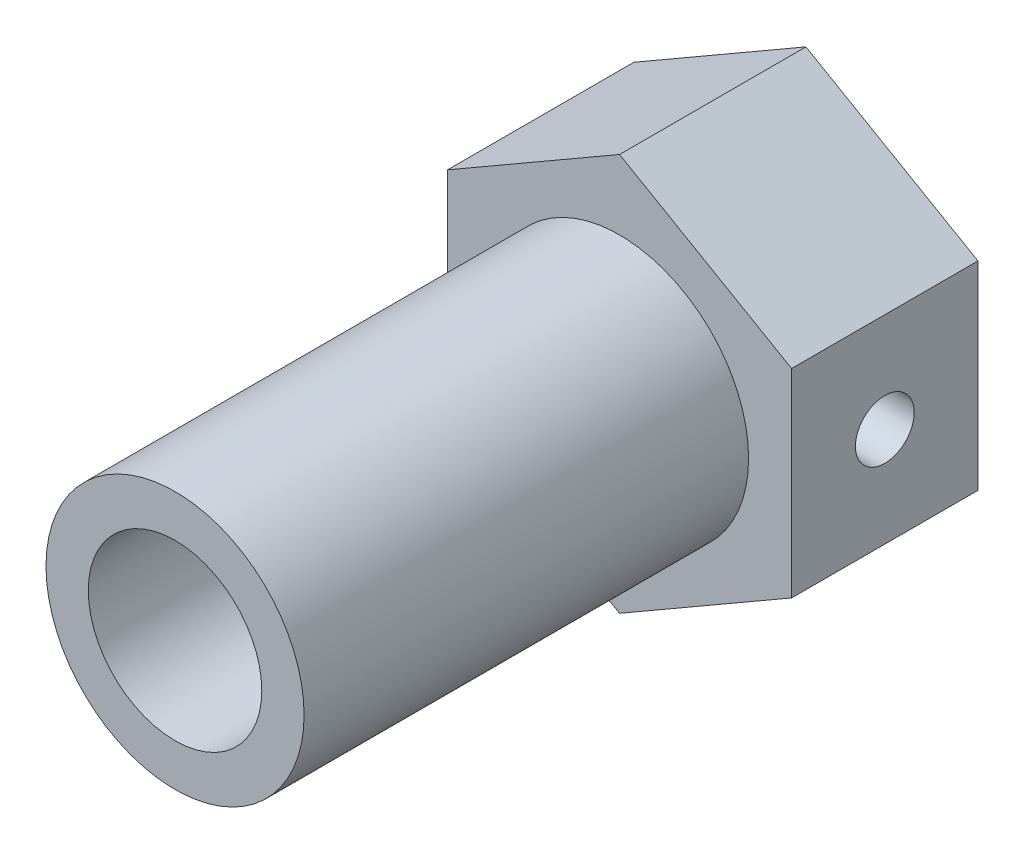
SolidWorks part; units mm, degrees
material "7050-T73510"
ref_plane "前视基准面" through (0, 0, 0) normal (0, 0, 1) x (1, 0, 0)
ref_plane "上视基准面" through (0, 0, 0) normal (0, 1, 0) x (1, 0, 0)
ref_plane "右视基准面" through (0, 0, 0) normal (1, 0, 0) x (0, 0, -1)
sketch "草图1" plane through (0, 0, 0) normal (0, 0, 1) x (1, 0, 0)
  line L1 (0, 13.8564) -> (-12, 6.9282)
  line L2 (-12, 6.9282) -> (-12, -6.9282)
  line L3 (-12, -6.9282) -> (0, -13.8564)
  line L4 (0, -13.8564) -> (12, -6.9282)
  line L5 (12, -6.9282) -> (12, 6.9282)
  line L6 (12, 6.9282) -> (0, 13.8564)
  circle A0 centre (0, 0) radius 12 construction
  dimension "D1" = 24
extrude "凸台-拉伸1" add sketch "草图1" along normal blind 13
sketch "草图2" plane through (0, 0, 13) normal (0, 0, 1) x (1, 0, 0)
  circle A0 centre (0, 0) radius 9
  dimension "D1" = 18
extrude "凸台-拉伸2" add sketch "草图2" along normal blind 31
sketch "草图3" plane through (0, 0, 0) normal (0, 0, -1) x (-1, 0, 0)
  circle A0 centre (0, 0) radius 8
  dimension "D1" = 16
extrude "凸台-拉伸3" add sketch "草图3" along normal blind 1
sketch "草图4" plane through (0, 0, -1) normal (0, 0, -1) x (-1, 0, 0)
  circle A0 centre (0, 0) radius 6.05
  dimension "D1" = 12.1
extrude "切除-拉伸1" cut sketch "草图4" against normal up to surface (45 mm away) up to face at (9, 0, 44)
sketch "草图5" plane through (0, 0, 0) normal (1, 0, 0) x (0, 0, -1)
  line L0 (0, -6.9282) -> (0, 6.9282) construction
  circle A0 centre (-6.5, 0) radius 2.05
  dimension "D1" = 6.5
  dimension "D2" = 4.1
extrude "切除-拉伸2" cut sketch "草图5" against normal mid plane 50
